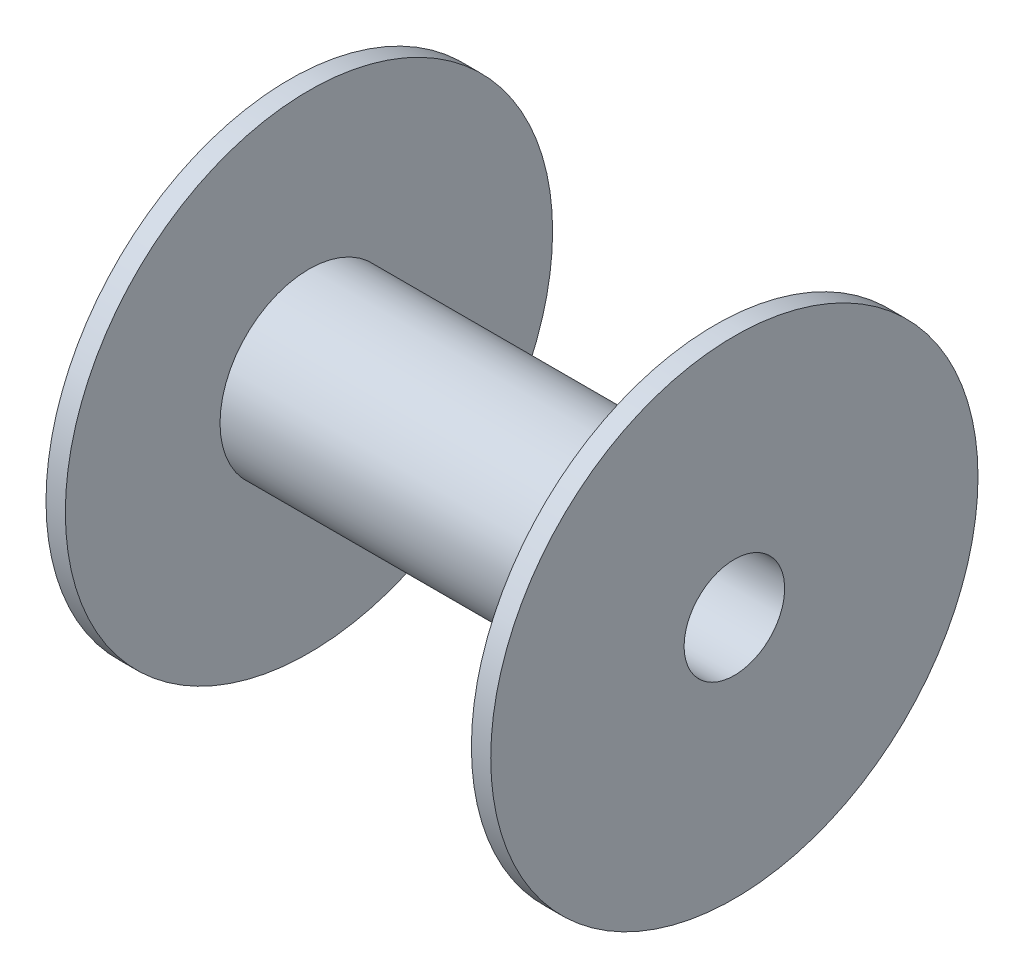
SolidWorks part; units mm, degrees
ref_plane "Front Plane" through (0, 0, 0) normal (0, 0, 1) x (1, 0, 0)
ref_plane "Top Plane" through (0, 0, 0) normal (0, 1, 0) x (1, 0, 0)
ref_plane "Right Plane" through (0, 0, 0) normal (1, 0, 0) x (0, 0, -1)
sketch "Sketch1" plane through (0, 0, 0) normal (0, 0, 1) x (1, 0, 0)
  line L0 (-70, 0) -> (70, 0) construction
  line L2 (-57.5, 63) -> (-52.5, 63)
  line L3 (-52.5, 63) -> (-52.5, 23)
  line L4 (-52.5, 23) -> (52.5, 23)
  line L12 (-57.5, 63) -> (-57.5, 13)
  line L13 (-57.5, 13) -> (57.5, 13)
  line L15 (0, 0) -> (0, 26) construction
  line L16 (57.5, 13) -> (57.5, 63)
  line L17 (57.5, 63) -> (52.5, 63)
  line L18 (52.5, 63) -> (52.5, 23)
  line L19 (70, 0) -> (70, 67.6816) construction
  line L20 (57.5, 13) -> (70, 13) construction
  point P4 (0, 0)
  point P14 (0, 13)
  point P15 (70, 13)
  dimension "D1" = 140
  dimension "D2" = 5
  dimension "D3" = 40
  dimension "D4" = 13
  dimension "D5" = 40
  dimension "D6" = 50
  dimension "D7" = 12.5
  dimension "D8" = 67.6816
  dimension "D9" = 5
revolve "Revolve1" add sketch "Sketch1" angle 360 about L0
